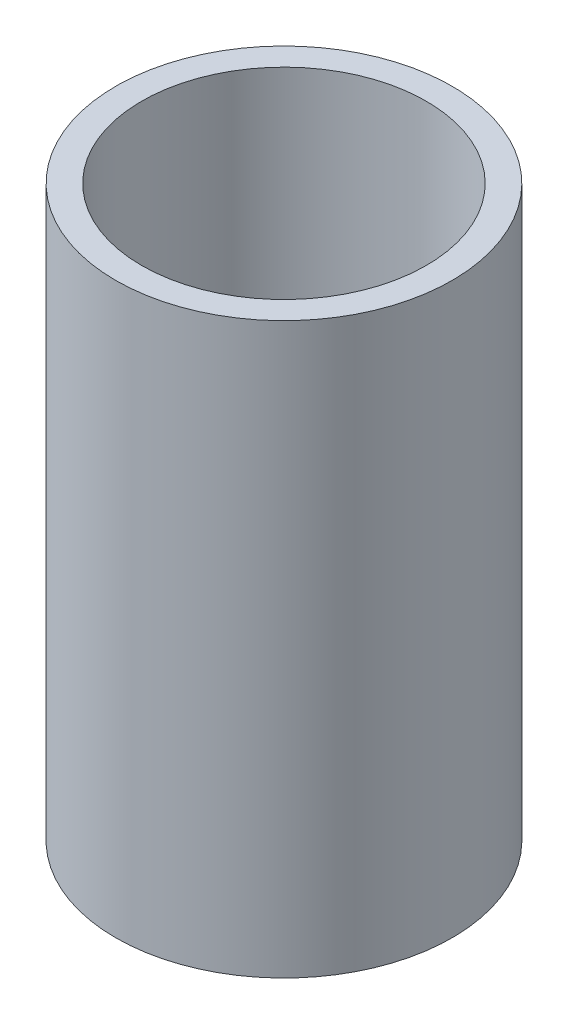
SolidWorks part; units mm, degrees
ref_plane "Front Plane" through (0, 0, 0) normal (0, 0, 1) x (1, 0, 0)
ref_plane "Top Plane" through (0, 0, 0) normal (0, 1, 0) x (1, 0, 0)
ref_plane "Right Plane" through (0, 0, 0) normal (1, 0, 0) x (0, 0, -1)
sketch "Sketch1" plane through (0, 0, 0) normal (0, 1, 0) x (1, 0, 0)
  circle A0 centre (0, 0) radius 3.25
  circle A1 centre (0, 0) radius 2.75
  dimension "D1" = 6.5
  dimension "D2" = 5.5
extrude "Boss-Extrude1" add sketch "Sketch1" along normal blind 11
